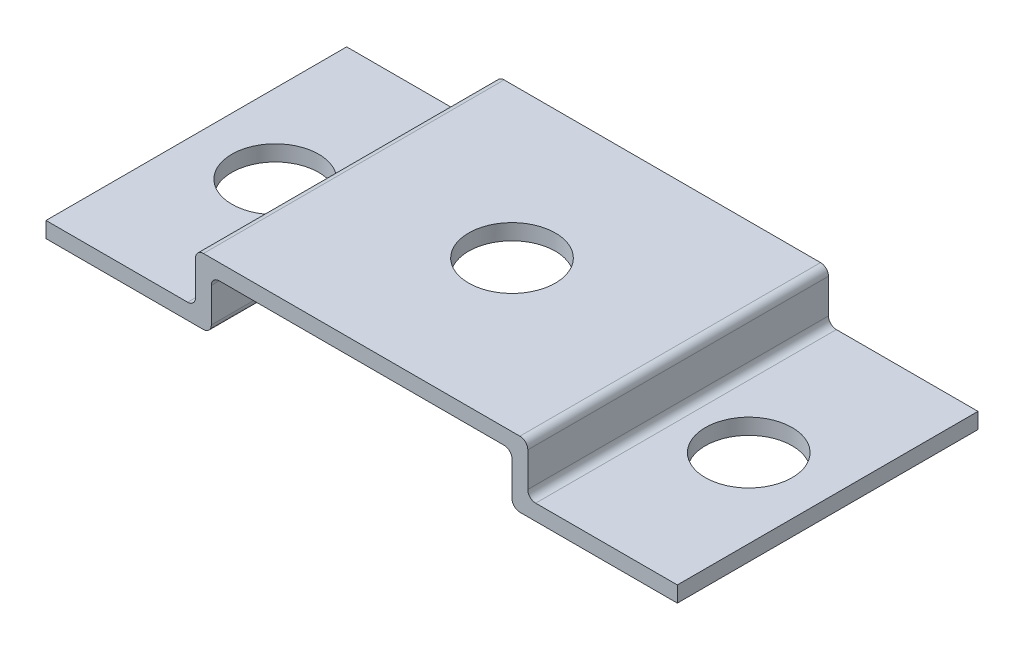
SolidWorks part; units mm, degrees
ref_plane "Front Plane" through (0, 0, 0) normal (0, 0, 1) x (1, 0, 0)
ref_plane "Top Plane" through (0, 0, 0) normal (0, 1, 0) x (1, 0, 0)
ref_plane "Right Plane" through (0, 0, 0) normal (1, 0, 0) x (0, 0, -1)
sketch "Sketch1" plane through (0, 0, 0) normal (0, 0, 1) x (1, 0, 0)
  line L0 (0, 0) -> (9.475, 0)
  line L1 (9.475, 0) -> (9.475, 3.175)
  line L2 (9.475, 3.175) -> (30.525, 3.175)
  line L3 (30.525, 3.175) -> (30.525, 0)
  line L4 (30.525, 0) -> (40, 0)
  line L5 (40, 0) -> (40, -1)
  line L6 (40, -1) -> (29.525, -1)
  line L7 (29.525, -1) -> (29.525, 2.175)
  line L8 (29.525, 2.175) -> (10.475, 2.175)
  line L9 (10.475, 2.175) -> (10.475, -1)
  line L10 (10.475, -1) -> (0, -1)
  line L11 (0, -1) -> (0, 0)
  dimension "D1" = 1
  dimension "D2" = 19.05
  dimension "D3" = 1
  dimension "D4" = 1
  dimension "D5" = 3.175
  dimension "D6" = 1
  dimension "D7" = 40
extrude "Boss-Extrude1" add sketch "Sketch1" against normal blind 19.05
fillet "Fillet1" radius 0.5 8 edges at (10.475, -1, -9.525) (29.525, -1, -9.525) (9.475, 0, -9.525) (30.525, 0, -9.525) (30.525, 3.175, -9.525) (29.525, 2.175, -9.525) (10.475, 2.175, -9.525) (9.475, 3.175, -9.525)
sketch "Sketch3" plane through (0, 0, 0) normal (0, 1, 0) x (1, 0, 0)
  line L3 (0, 9.525) -> (8.975, 9.525) construction
  line L4 (0, 19.05) -> (0, 0) construction
  line L5 (8.975, 0) -> (8.975, 19.05) construction
  line L6 (20, 19.05) -> (20, 0) construction
  line L7 (30.025, 19.05) -> (9.975, 19.05) construction
  line L8 (30.025, 0) -> (9.975, 0) construction
  circle A2 centre (5, 9.525) radius 2.75
  circle A3 centre (35, 9.525) radius 2.75
  dimension "D1" = 5.5
  dimension "D2" = 5
extrude "Cut-Extrude1" cut sketch "Sketch3" against normal through all
sketch "Sketch4" plane through (0, 3.175, 0) normal (0, 1, 0) x (1, 0, 0)
  line L0 (20, 19.05) -> (20, 0) construction
  line L1 (30.025, 19.05) -> (9.975, 19.05) construction
  line L2 (29.525, 0) -> (10.475, 0) construction
  line L3 (20, 0) -> (9.975, 9.525) construction
  line L4 (9.975, 19.05) -> (9.975, 0) construction
  line L5 (9.975, 9.525) -> (30.025, 9.525) construction
  line L6 (30.025, 0) -> (30.025, 19.05) construction
  circle A0 centre (20, 9.525) radius 2.75
  circle A1 centre (5, 9.525) radius 2.75 construction
extrude "Cut-Extrude2" cut sketch "Sketch4" against normal through all
